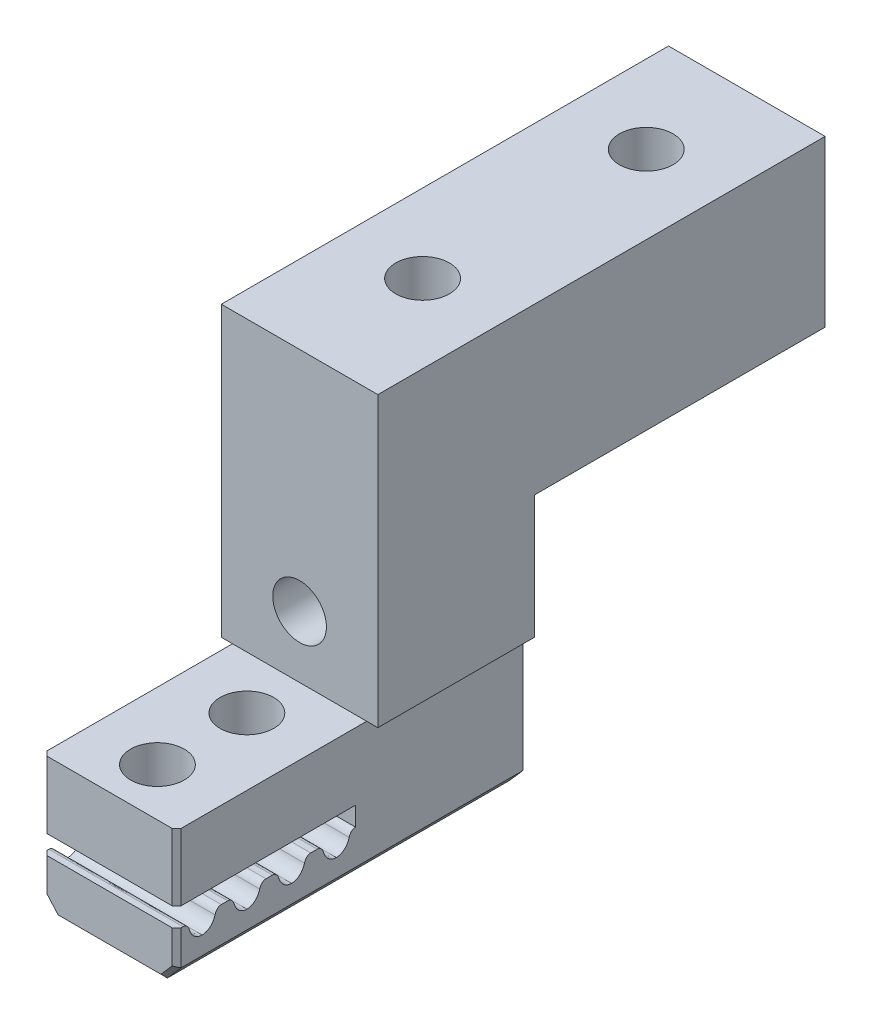
SolidWorks part; units mm, degrees
ref_plane "Front Plane" through (0, 0, 0) normal (0, 0, 1) x (1, 0, 0)
ref_plane "Top Plane" through (0, 0, 0) normal (0, 1, 0) x (1, 0, 0)
ref_plane "Right Plane" through (0, 0, 0) normal (1, 0, 0) x (0, 0, -1)
sketch "Sketch1" plane through (0, 0, 0) normal (0, 0, 1) x (1, 0, 0)
  line L0 (3, 3.05) -> (3, -2.2538)
  line L1 (-3, 3.05) -> (-3, -2.2538)
  line L7 (-3, 3.05) -> (3, 3.05)
  line L13 (-3, -2.2538) -> (-2.3882, -2.95)
  line L14 (3, -2.2538) -> (2.3882, -2.95)
  line L16 (-2.3882, -2.95) -> (2.3882, -2.95)
extrude "Boss-Extrude1" add sketch "Sketch1" along normal blind 13
sketch "Sketch6" plane through (0, 3.05, 0) normal (0, 1, 0) x (1, 0, 0)
  line L0 (-3, -5) -> (-3, 0)
  line L1 (-3, 0) -> (3, 0)
  line L3 (-3, -5) -> (3, -5)
  line L6 (3, -5) -> (3, 0)
  line L7 (3, 0) -> (-3, 0) construction
extrude "Boss-Extrude4" add sketch "Sketch6" along normal blind 5.6
sketch "Sketch16" plane through (0, 3.05, 0) normal (0, 1, 0) x (1, 0, 0)
  line L4 (3, -5) -> (-3, -5)
  line L5 (-3, -5) -> (-3, -13)
  line L6 (-3, -13) -> (3, -13)
  line L7 (3, -13) -> (3, -5)
  line L8 (3, -5) -> (-3, -5)
  line L9 (-3, -5) -> (-3, -13)
  line L10 (-3, -13) -> (3, -13)
  line L11 (3, -13) -> (3, -5)
  dimension "D1" = 0
extrude "Boss-Extrude5" add sketch "Sketch16" along normal blind 0.1
sketch "Sketch18" plane through (0, 0, 0) normal (1, 0, 0) x (0, 0, -1)
  line L0 (-8.8572, -0.0702) -> (-12.8572, -0.0702)
  line L2 (-12.8572, -0.7) -> (-12.7144, -0.7)
  line L3 (-11, -0.7) -> (-10.8572, -0.7)
  line L4 (-10.8572, -0.7) -> (-10.7144, -0.7)
  line L5 (-9, -0.7) -> (-8.8572, -0.7)
  line L6 (-8.8572, -0.7) -> (-8.7144, -0.7)
  line L7 (-7, -0.7) -> (-6.8572, -0.7)
  line L8 (-6.8572, -0.7) -> (-6.7144, -0.7)
  line L9 (-5, -0.0702) -> (-5, -0.7)
  line L11 (-5, -0.0702) -> (-8.8572, -0.0702)
  line L12 (-13, -2.95) -> (0, -2.95) construction
  line L13 (-5.8572, -1.45) -> (-5, -1.45) construction
  line L14 (-5, -1.45) -> (-11.8572, -1.45) construction
  line L15 (-5, 3.15) -> (-5, -1.45) construction
  line L16 (-5, -0.7) -> (-5, -1.45) construction
  line L17 (-12.8572, -0.0702) -> (-13, -0.0702)
  line L20 (-13, -0.0702) -> (-13, -0.7)
  line L22 (-12.8572, -0.7) -> (-13, -0.7)
  spline S0 degree 2 poles (-12.7144, -0.7) (-12.5198, -0.7) (-12.43, -0.9509) knots 0.103448 0.103448 0.103448 0.137931 0.137931 0.137931
  spline S1 degree 3 poles (-12.43, -0.9509) (-12.3594, -1.2388) (-12.13, -1.45) (-11.8572, -1.45) knots 0.137931 0.137931 0.137931 0.137931 0.172414 0.172414 0.172414 0.172414
  spline S2 degree 3 poles (-11.8572, -1.45) (-11.5844, -1.45) (-11.355, -1.2388) (-11.2844, -0.9509) knots 0.172414 0.172414 0.172414 0.172414 0.206897 0.206897 0.206897 0.206897
  spline S3 degree 2 poles (-11.2844, -0.9509) (-11.1946, -0.7) (-11, -0.7) knots 0.206897 0.206897 0.206897 0.241379 0.241379 0.241379
  spline S4 degree 2 poles (-10.7144, -0.7) (-10.5198, -0.7) (-10.43, -0.9509) knots 0.310345 0.310345 0.310345 0.344828 0.344828 0.344828
  spline S5 degree 3 poles (-10.43, -0.9509) (-10.3594, -1.2388) (-10.13, -1.45) (-9.8572, -1.45) knots 0.344828 0.344828 0.344828 0.344828 0.37931 0.37931 0.37931 0.37931
  spline S6 degree 3 poles (-9.8572, -1.45) (-9.5844, -1.45) (-9.355, -1.2388) (-9.2844, -0.9509) knots 0.37931 0.37931 0.37931 0.37931 0.413793 0.413793 0.413793 0.413793
  spline S7 degree 2 poles (-9.2844, -0.9509) (-9.1946, -0.7) (-9, -0.7) knots 0.413793 0.413793 0.413793 0.448276 0.448276 0.448276
  spline S8 degree 2 poles (-8.7144, -0.7) (-8.5198, -0.7) (-8.43, -0.9509) knots 0.517241 0.517241 0.517241 0.551724 0.551724 0.551724
  spline S9 degree 3 poles (-8.43, -0.9509) (-8.3594, -1.2388) (-8.13, -1.45) (-7.8572, -1.45) knots 0.551724 0.551724 0.551724 0.551724 0.586207 0.586207 0.586207 0.586207
  spline S10 degree 3 poles (-7.8572, -1.45) (-7.5844, -1.45) (-7.355, -1.2388) (-7.2844, -0.9509) knots 0.586207 0.586207 0.586207 0.586207 0.62069 0.62069 0.62069 0.62069
  spline S11 degree 2 poles (-7.2844, -0.9509) (-7.1946, -0.7) (-7, -0.7) knots 0.62069 0.62069 0.62069 0.655172 0.655172 0.655172
  spline S12 degree 2 poles (-6.7144, -0.7) (-6.5198, -0.7) (-6.43, -0.9509) knots 0.724138 0.724138 0.724138 0.758621 0.758621 0.758621
  spline S13 degree 3 poles (-6.43, -0.9509) (-6.3594, -1.2388) (-6.13, -1.45) (-5.8572, -1.45) knots 0.758621 0.758621 0.758621 0.758621 0.793103 0.793103 0.793103 0.793103
  spline S14 degree 3 poles (-5.8572, -1.45) (-5.5844, -1.45) (-5.355, -1.2388) (-5.2844, -0.9509) knots 0.793103 0.793103 0.793103 0.793103 0.827586 0.827586 0.827586 0.827586
  spline S15 degree 2 poles (-5.2844, -0.9509) (-5.1946, -0.7) (-5, -0.7) knots 0.827586 0.827586 0.827586 0.862069 0.862069 0.862069
  dimension "D1" = 1.5
  dimension "D2" = 1.3798
extrude "Cut-Extrude6" cut sketch "Sketch18" against normal blind 3.6 and the other way blind 4
sketch "Sketch15" plane through (0, 8.65, 0) normal (0, 1, 0) x (1, 0, 0)
  line L0 (0, -13) -> (0, -5) construction
  line L1 (-3, -13) -> (3, -13) construction
  line L2 (-3, -5) -> (3, -5) construction
  line L3 (2.008, -10.7144) -> (2.008, -11) construction
  line L4 (3, -10.7144) -> (-3, -10.7144) construction
  line L5 (3, -11) -> (-3, -11) construction
  line L6 (2.008, -10.8572) -> (0, -10.8572) construction
  line L7 (1.0382, -6.7144) -> (1.0382, -7) construction
  line L8 (3, -6.7144) -> (-3, -6.7144) construction
  line L9 (3, -7) -> (-3, -7) construction
  line L10 (1.0382, -6.8572) -> (0, -6.8572) construction
  circle A0 centre (0, -6.8572) radius 1.5 construction
  circle A1 centre (0, -10.8572) radius 1.5 construction
  circle A2 centre (0, -10.8572) radius 1.2
  circle A4 centre (0, -6.8572) radius 1.2
extrude "Cut-Extrude7" cut sketch "Sketch15" against normal up to surface (8.7202 mm away) up to face at (0, -0.0702, 9)
sketch "Sketch19" plane through (0, -0.0702, 0) normal (0, -1, 0) x (1, 0, 0)
  line L4 (-3, 13) -> (-3, 5)
  line L5 (-3, 5) -> (3, 5)
  line L6 (3, 5) -> (3, 13)
  line L7 (3, 13) -> (-3, 13)
  line L8 (-3, 13) -> (-3, 5)
  line L9 (-3, 5) -> (3, 5)
  line L10 (3, 5) -> (3, 13)
  line L11 (3, 13) -> (-3, 13)
  circle A0 centre (0, 10.8572) radius 1.2 construction
  circle A1 centre (0, 6.8572) radius 1.2 construction
  circle A2 centre (0, 10.8572) radius 1.2
  circle A3 centre (0, 6.8572) radius 1.2
  dimension "D1" = 0
extrude "Cut-Extrude8" cut sketch "Sketch19" against normal blind 0.2202
sketch "Sketch12" plane through (0, 0, 5) normal (0, 0, 1) x (1, 0, 0)
  circle A0 centre (0, 5.85) radius 1.5 construction
  circle A1 centre (0, 5.85) radius 1.2
extrude "Cut-Extrude5" cut sketch "Sketch12" against normal blind 6
chamfer "Chamfer1" distance 0.2 angle 45 7 edges at (-3, 1.65, 13) (-3, -1.4769, 13) (-2.6941, -2.6019, 13) (0, -2.95, 13) (2.6941, -2.6019, 13) (3, -1.4769, 13) (3, 1.65, 13)
sketch "Sketch21" plane through (0, 0, 0) normal (0, 0, -1) x (-1, 0, 0)
  line L10 (-2.3882, -2.95) -> (2.3882, -2.95)
  line L11 (2.3882, -2.95) -> (3, -2.2538)
  line L12 (3, -2.2538) -> (3, 8.65)
  line L13 (3, 8.65) -> (-3, 8.65)
  line L14 (-3, 8.65) -> (-3, -2.2538)
  line L15 (-3, -2.2538) -> (-2.3882, -2.95)
  line L19 (-2.3882, -2.95) -> (2.3882, -2.95)
  line L20 (2.3882, -2.95) -> (3, -2.2538)
  line L21 (3, -2.2538) -> (3, 8.65)
  line L22 (3, 8.65) -> (-3, 8.65)
  line L23 (-3, 8.65) -> (-3, -2.2538)
  line L24 (-3, -2.2538) -> (-2.3882, -2.95)
  circle A0 centre (0, 5.85) radius 1.2 construction
  circle A1 centre (0, 5.85) radius 1.2
  dimension "D1" = 0
extrude "Boss-Extrude6" add sketch "Sketch21" along normal blind 2.5
sketch "Sketch24" plane through (0, 0, 5) normal (0, 0, 1) x (1, 0, 0)
  line L4 (-3, 8.65) -> (-3, 3.15)
  line L5 (-3, 3.15) -> (3, 3.15)
  line L6 (3, 3.15) -> (3, 8.65)
  line L7 (3, 8.65) -> (-3, 8.65)
  line L8 (-3, 8.65) -> (-3, 3.15)
  line L9 (-3, 3.15) -> (3, 3.15)
  line L10 (3, 3.15) -> (3, 8.65)
  line L11 (3, 8.65) -> (-3, 8.65)
  dimension "D1" = 0
extrude "Cut-Extrude10" cut sketch "Sketch24" against normal blind 8.5
sketch "Sketch25" plane through (0, 3.15, 0) normal (0, 1, 0) x (1, 0, 0)
  line L0 (3, -12.8) -> (3, 2.5) construction
  line L2 (-3, 2.5) -> (3, 2.5)
  line L3 (-3, 2.5) -> (-3, -4.5)
  line L4 (-3, -4.5) -> (3, -4.5)
  line L5 (3, 2.5) -> (3, -4.5)
  dimension "D1" = 7
extrude "Boss-Extrude8" add sketch "Sketch25" along normal blind 12.9
sketch "Sketch26" plane through (0, 0, -2.5) normal (0, 0, -1) x (-1, 0, 0)
  line L0 (3, -2.2538) -> (3, 16.05) construction
  line L1 (-3, 16.05) -> (3, 16.05)
  line L2 (-3, 16.05) -> (-3, 8.66)
  line L3 (-3, 8.66) -> (3, 8.66)
  line L4 (3, 16.05) -> (3, 8.66)
extrude "Boss-Extrude9" add sketch "Sketch26" along normal blind 5
sketch "Sketch27" plane through (0, 0, -7.5) normal (0, 0, -1) x (-1, 0, 0)
  line L4 (-3, 16.05) -> (-3, 8.66)
  line L5 (-3, 8.66) -> (3, 8.66)
  line L6 (3, 8.66) -> (3, 16.05)
  line L7 (3, 16.05) -> (-3, 16.05)
  line L8 (-3, 16.05) -> (-3, 8.66)
  line L9 (-3, 8.66) -> (3, 8.66)
  line L10 (3, 8.66) -> (3, 16.05)
  line L11 (3, 16.05) -> (-3, 16.05)
  dimension "D1" = 0
extrude "Boss-Extrude10" add sketch "Sketch27" along normal blind 8
sketch "Sketch28" plane through (0, 16.05, 0) normal (0, 1, 0) x (1, 0, 0)
  circle A2 centre (0, 1) radius 1.2 construction
  circle A3 centre (0, 11) radius 1.2
extrude "Cut-Extrude11" cut sketch "Sketch28" against normal blind 7.5
sketch "Sketch30" plane through (0, 0, -2.5) normal (0, 0, -1) x (-1, 0, 0)
  circle A2 centre (0, 5.9) radius 1.2
extrude "Cut-Extrude13" cut sketch "Sketch30" against normal blind 8
sketch "Sketch31" plane through (3, 0, 0) normal (1, 0, 0) x (0, 0, -1)
  line L1 (-4.5, 16.05) -> (2.5, 16.05)
  line L2 (-4.5, 16.05) -> (-4.5, 3.15)
  line L3 (-4.5, 3.15) -> (2.5, 3.15)
  line L4 (2.5, 16.05) -> (2.5, 3.15)
  line L5 (-12.8, 3.15) -> (-4.5, 3.15) construction
extrude "Boss-Extrude11" add sketch "Sketch31" along normal blind 0.5
sketch "Sketch32" plane through (-3, 0, 0) normal (-1, 0, 0) x (0, 0, 1)
  line L0 (-2.5, -2.2538) -> (-2.5, 8.66) construction
  line L1 (4.5, 16.05) -> (-2.5, 16.05)
  line L2 (4.5, 16.05) -> (4.5, 3.15)
  line L3 (4.5, 3.15) -> (-2.5, 3.15)
  line L4 (-2.5, 16.05) -> (-2.5, 3.15)
  line L6 (4.5, 3.15) -> (12.8, 3.15) construction
extrude "Boss-Extrude12" add sketch "Sketch32" along normal blind 0.5
sketch "Sketch33" plane through (0, 0, -2.5) normal (0, 0, -1) x (-1, 0, 0)
  line L1 (-3, 8.66) -> (-3.5, 8.66)
  line L2 (-3, 8.66) -> (-3, 16.05)
  line L3 (-3, 16.05) -> (-3.5, 16.05)
  line L4 (-3.5, 8.66) -> (-3.5, 16.05)
  line L5 (3, 8.66) -> (3.5, 8.66)
  line L6 (3, 8.66) -> (3, 16.05)
  line L7 (3, 16.05) -> (3.5, 16.05)
  line L8 (3.5, 8.66) -> (3.5, 16.05)
extrude "Boss-Extrude13" add sketch "Sketch33" along normal up to surface (13 mm away) up to face at (0, 12.355, -15.5)
sketch "Sketch34" plane through (0, 16.05, 0) normal (0, 1, 0) x (1, 0, 0)
  circle A0 centre (0, 1) radius 1.2
extrude "Cut-Extrude14" cut sketch "Sketch34" against normal blind 5
